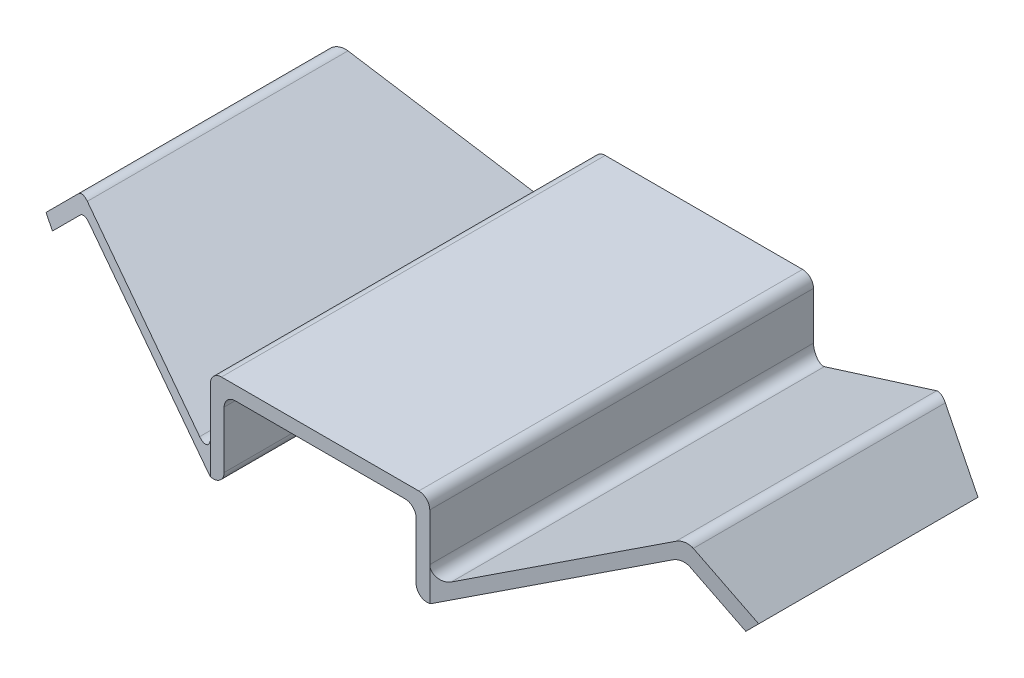
SolidWorks part; units mm, degrees
ref_plane "Front Plane" through (0, 0, 0) normal (0, 0, 1) x (1, 0, 0)
ref_plane "Top Plane" through (0, 0, 0) normal (0, 1, 0) x (1, 0, 0)
ref_plane "Right Plane" through (0, 0, 0) normal (1, 0, 0) x (0, 0, -1)
sketch "Sketch1" plane through (0, 0, 0) normal (0, 0, 1) x (1, 0, 0)
  line L0 (-1, 0) -> (1, 0)
  line L1 (-1, 0) -> (-1, -0.7)
  line L2 (-1, -0.7) -> (-2.75, 0.25)
  line L3 (-2.75, 0.25) -> (-3.25, -0.25)
  line L4 (1, 0) -> (1, -0.7)
  line L5 (1, -0.7) -> (2.75, 0.25)
  line L6 (2.75, 0.25) -> (3.25, -0.25)
  line L7 (0, 0) -> (0, -5.2603) construction
  line L8 (-2.7276, 0.0956) -> (-3.1616, -0.3384)
  line L9 (-0.875, -0.9101) -> (-2.7276, 0.0956)
  line L10 (-0.875, -0.125) -> (-0.875, -0.9101)
  line L11 (-0.875, -0.125) -> (0.875, -0.125)
  line L12 (0.875, -0.125) -> (0.875, -0.9101)
  line L13 (0.875, -0.9101) -> (2.7276, 0.0956)
  line L14 (2.7276, 0.0956) -> (3.1616, -0.3384)
  line L15 (-3.25, -0.25) -> (-3.1616, -0.3384)
  line L16 (3.1616, -0.3384) -> (3.25, -0.25)
  dimension "D1" = 2
  dimension "D2" = 5.5
  dimension "D3" = 0.25
  dimension "D4" = 6.5
  dimension "D5" = 0.7
  dimension "D6" = 0.5
  dimension "D7" = 0.125
extrude "Boss-Extrude1" add sketch "Sketch1" along normal mid plane 3.5
sketch "Sketch2" plane through (0, 0, 0) normal (0, 1, 0) x (1, 0, 0)
  line L0 (-3.25, 1) -> (-1, 1.75)
  line L1 (-3.25, -1.75) -> (-3.25, 1.75) construction
  line L3 (-3.25, 1) -> (-3.25, 1.75)
  line L4 (-3.25, 1.75) -> (-1, 1.75)
  point P6 (-3.25, 0)
  point P10 (0, 0)
  dimension "D1" = 1
  dimension "D2" = 1
extrude "Cut-Extrude1" cut sketch "Sketch2" against normal through all both and the other way through all
mirror "Mirror1" about plane through (0, 0, 0) normal (0, 0, 1) of "Cut-Extrude1"
mirror "Mirror2" about plane through (0, 0, 0) normal (1, 0, 0) of "Mirror1", "Cut-Extrude1"
fillet "Fillet1" radius 0.1 12 edges at (1, 0, 0) (-1, 0, 0) (0.875, -0.125, 0) (-0.875, -0.125, 0) (0.875, -0.9101, 0) (-0.875, -0.9101, 0) (2.7276, 0.0956, 0) (-2.7276, 0.0956, 0) (2.75, 0.25, 0) (-2.75, 0.25, 0) (1, -0.7, 0) (-1, -0.7, 0)
